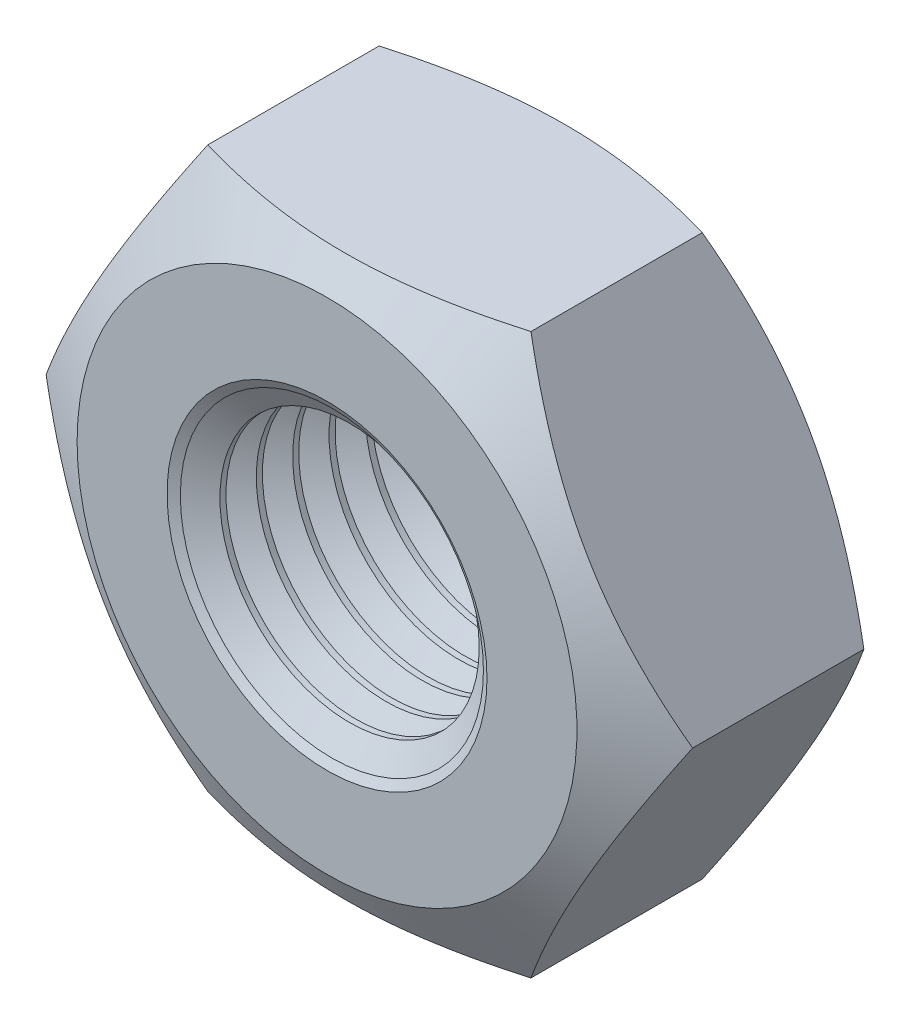
SolidWorks part; units mm, degrees
ref_plane "Front" through (0, 0, 0) normal (0, 0, 1) x (1, 0, 0)
ref_plane "Top" through (0, 0, 0) normal (0, 1, 0) x (1, 0, 0)
ref_plane "Right" through (0, 0, 0) normal (1, 0, 0) x (0, 0, -1)
sketch "Sketch1" plane through (0, 0, 0) normal (0, 0, 1) x (1, 0, 0)
  line L1 (4.0415, 0) -> (2.0207, 3.5)
  line L2 (2.0207, 3.5) -> (-2.0207, 3.5)
  line L3 (-2.0207, 3.5) -> (-4.0415, 0)
  line L4 (-4.0415, 0) -> (-2.0207, -3.5)
  line L5 (-2.0207, -3.5) -> (2.0207, -3.5)
  line L6 (2.0207, -3.5) -> (4.0415, 0)
  circle A0 centre (0, 0) radius 3.5 construction
  circle A1 centre (0, 0) radius 1.621
  dimension "D" = 3.242
  dimension "s" = 7
extrude "BaseNut" add sketch "Sketch1" against normal blind 3.2
cosmetic thread "ThreadCosmetic1" [suppressed] parameters "D"=4
sketch "Sketch2" plane through (0, 0, 0) normal (0, 1, 0) x (1, 0, 0)
  line L0 (-4.0415, 3.2) -> (-3.125, 3.2)
  line L2 (-3.125, 3.2) -> (-4.0415, 2.6709)
  line L3 (-4.0415, 2.6709) -> (-4.0415, 3.2)
  line L4 (0, 3.3759) -> (0, -9.8171) construction
  line L6 (-9.7712, 1.6) -> (9.8853, 1.6) construction
  line L7 (-4.0415, 0.5291) -> (-4.0415, 0)
  line L8 (-3.125, 0) -> (-4.0415, 0.5291)
  line L9 (-4.0415, 0) -> (-3.125, 0)
  dimension "dw" = 6.25
  dimension "D1" = 30
  dimension "D2" = 1.6
revolve "Double-Chamfer" cut sketch "Sketch2" angle 360 about L4
chamfer "EndChamfer" distance 0.379 angle 30 2 edges at (1.621, 0, -3.2) (1.621, 0, 0)
sketch "Sketch3" plane through (0, 0, 0) normal (0, 1, 0) x (1, 0, 0)
  line L0 (-1.9492, 2.821) -> (-1.621, 2.6315)
  line L1 (-1.621, 2.6315) -> (-1.242, 2.6315)
  line L2 (-1.242, 2.6315) -> (-1.242, 3.0105)
  line L3 (-1.242, 3.0105) -> (-1.621, 3.0105)
  line L4 (-1.621, 3.0105) -> (-1.9492, 2.821)
  line L5 (0, 7.4383) -> (0, 16.8806) construction
  dimension "D1" = 0.379
  dimension "D2" = 3.242
revolve "Cut-Revolve10" cut sketch "Sketch3" angle 360 about L5
pattern_linear "LPattern10" count 7 spacing 0.4548 along (0, 0, 1) of "Cut-Revolve10"
equation "\"dw@Sketch2\" = \"s@Sketch1\"-0.75"
equation "\"D2@Sketch2\" = \"m@BaseNut\" / 2"
equation "\"D2@Sketch3\" = \"D@Sketch1\""
equation "\"D1@Sketch3\" =  (\"D@ThreadCosmetic1\"   - \"D@Sketch1\")  / 2"
equation "\"D3@LPattern10\" = \"D1@Sketch3\" * 1.2"
equation "\"D1@LPattern10\" = \"m@BaseNut\"/\"D3@LPattern10\""
